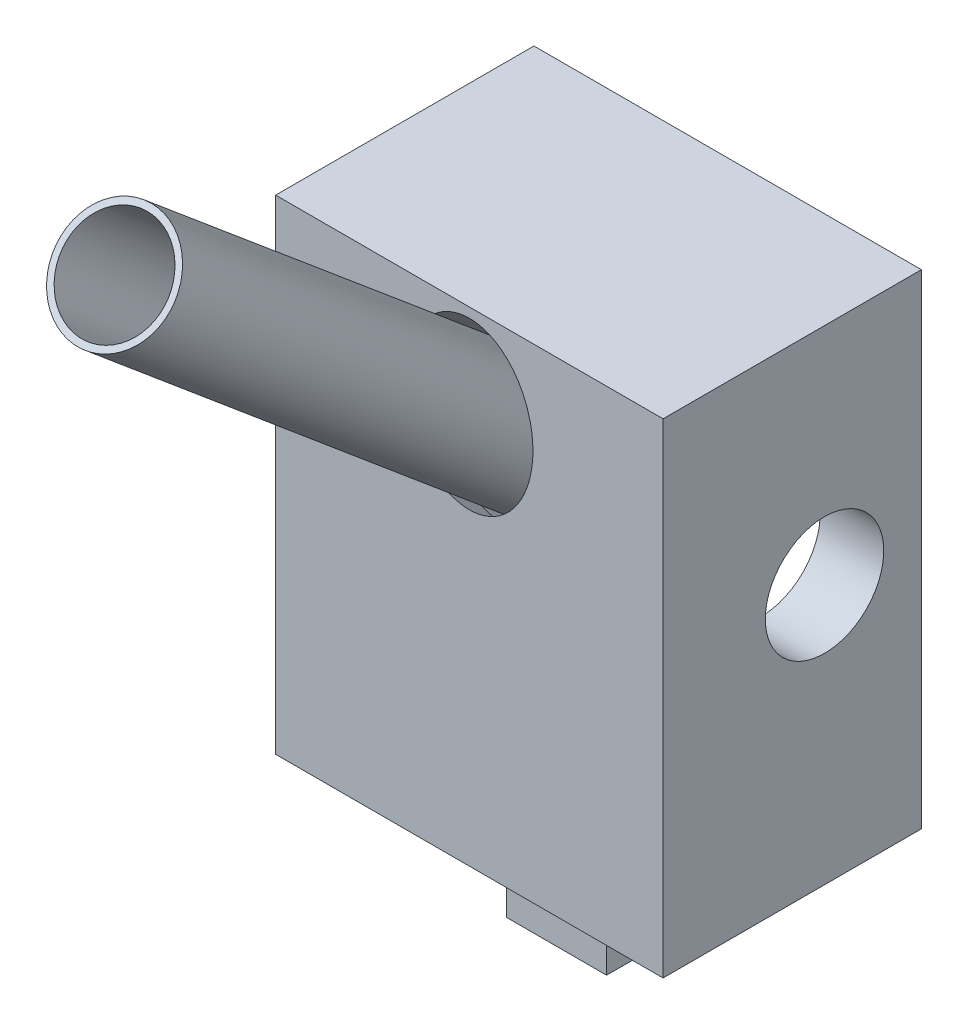
SolidWorks part; units mm, degrees
ref_plane "Front Plane" through (0, 0, 0) normal (0, 0, 1) x (1, 0, 0)
ref_plane "Top Plane" through (0, 0, 0) normal (0, 1, 0) x (1, 0, 0)
ref_plane "Right Plane" through (0, 0, 0) normal (1, 0, 0) x (0, 0, -1)
sketch "Sketch1" plane through (0, 0, 0) normal (0, 0, 1) x (1, 0, 0)
  line L1 (6066.2942, -5703.2258) -> (6096.7742, -5703.2258)
  line L2 (6066.2942, -5703.2258) -> (6066.2942, -5741.3258)
  line L3 (6066.2942, -5741.3258) -> (6096.7742, -5741.3258)
  line L4 (6096.7742, -5703.2258) -> (6096.7742, -5741.3258)
  dimension "D1" = 38.1
  dimension "D2" = 30.48
extrude "Boss-Extrude1" add sketch "Sketch1" along normal blind 20.32 from offset 7.5
sketch "Sketch2" plane through (0, 0, 7.5) normal (0, 0, -1) x (-1, 0, 0)
  line L0 (-6091.7742, -5710.8458) -> (-6096.7742, -5710.8458) construction
  line L1 (-6091.7742, -5710.8458) -> (-6071.3742, -5710.8458)
  line L2 (-6091.7742, -5710.8458) -> (-6091.7742, -5733.7058)
  line L3 (-6091.7742, -5733.7058) -> (-6071.3742, -5733.7058)
  line L4 (-6071.3742, -5710.8458) -> (-6071.3742, -5733.7058)
  line L5 (-6096.7742, -5741.3258) -> (-6096.7742, -5703.2258) construction
  line L6 (-6091.7742, -5710.8458) -> (-6091.7742, -5703.2258) construction
  line L7 (-6096.7742, -5703.2258) -> (-6066.2942, -5703.2258) construction
  line L8 (-6071.3742, -5710.8458) -> (-6066.2942, -5710.8458) construction
  line L9 (-6066.2942, -5703.2258) -> (-6066.2942, -5741.3258) construction
  line L10 (-6091.7742, -5733.7058) -> (-6091.7742, -5741.3258) construction
  line L11 (-6066.2942, -5741.3258) -> (-6096.7742, -5741.3258) construction
  dimension "D1" = 5
  dimension "D2" = 5.08
  dimension "D3" = 7.62
extrude "Cut-Extrude1" cut sketch "Sketch2" against normal blind 17.78
ref_plane "Plane3" through (0, -2342.7368, -2791.965) normal (0, -0.6428, -0.766) x (-1, 0, 0)
sketch "Sketch5" plane through (0, -2342.7368, -2791.965) normal (0, -0.6428, -0.766) x (-1, 0, 0)
  line L0 (-6081.5342, -4392.3948) -> (-6096.7742, -4392.3948) construction
  line L2 (-6081.5342, -4392.3948) -> (-6066.2942, -4392.3948) construction
  line L4 (-6066.2942, -4386.8068) -> (-6066.2942, -4415.9931) construction
  line L5 (-6096.7742, -4415.9931) -> (-6096.7742, -4386.8068) construction
  line L6 (-6081.5342, -4392.3948) -> (-6081.5342, -4386.8068) construction
  line L9 (-6096.7742, -4386.8068) -> (-6066.2942, -4386.8068) construction
  circle A0 centre (-6081.5342, -4392.3948) radius 5
  point P2 (-6081.5342, -4392.3948)
  point P5 (-6081.5342, -4386.8068)
  point P6 (-6081.5342, -4391.3807)
  point P7 (-6081.5342, -4392.4626)
  point P10 (0, 0)
  point P13 (-6081.5342, -4394.3882)
  point P14 (-6081.5342, -4386.8068)
  dimension "D1" = 10
  dimension "D2" = 5.588
extrude "Cut-Extrude2" cut sketch "Sketch5" along normal blind 23
sketch "Sketch10" plane through (0, -2342.7368, -2791.965) normal (0, -0.6428, -0.766) x (-1, 0, 0)
  line L0 (-6081.5342, -4392.3948) -> (-6096.7742, -4392.3948) construction
  line L2 (-6081.5342, -4392.3948) -> (-6066.2942, -4392.3948) construction
  circle A0 centre (-6081.5342, -4392.3948) radius 4.5
  circle A3 centre (-6081.5342, -4392.3948) radius 5 construction
  point P2 (-6084.5337, -4401.1393)
  dimension "D1" = 9
extrude "Boss-Extrude2" add sketch "Sketch10" against normal blind 31.75 and the other way blind 21.59 separate body
sketch "Sketch11" plane through (0, -2356.6146, -2808.5039) normal (0, -0.6428, -0.766) x (1, 0, 0)
  line L0 (6081.5342, 4387.8948) -> (6081.5342, 4392.3948) construction
  line L1 (6086.0342, 4392.3948) -> (6071.072, 4392.3948) construction
  circle A0 centre (6081.5342, 4392.3948) radius 4.5 construction
  circle A1 centre (6081.5342, 4392.3948) radius 4
  dimension "D1" = 8
extrude "Cut-Extrude6" cut sketch "Sketch11" against normal through all
hole_wizard "CSK for M3 Flat Head Machine Screw1" positions "Sketch13" profile "Sketch14" countersink size "M3" standard "ANSI Metric"
sketch "Sketch13" plane through (0, 0, 7.5) normal (0, 0, -1) x (-1, 0, 0)
  line L8 (-6070.1042, -5707.0358) -> (-6070.1042, -5703.2258) construction
  line L9 (-6096.7742, -5703.2258) -> (-6066.2942, -5703.2258) construction
  line L11 (-6070.1042, -5707.0358) -> (-6066.2942, -5707.0358) construction
  line L12 (-6066.2942, -5703.2258) -> (-6066.2942, -5741.3258) construction
  line L14 (-6096.7742, -5707.0358) -> (-6092.9642, -5707.0358) construction
  line L15 (-6096.7742, -5741.3258) -> (-6096.7742, -5703.2258) construction
  line L16 (-6092.9642, -5707.0358) -> (-6092.9642, -5703.2258) construction
  line L18 (-6096.7742, -5737.5158) -> (-6092.9642, -5737.5158) construction
  line L19 (-6092.9642, -5737.5158) -> (-6092.9642, -5741.3258) construction
  line L20 (-6066.2942, -5741.3258) -> (-6096.7742, -5741.3258) construction
  line L22 (-6070.1042, -5737.5158) -> (-6070.1042, -5741.3258) construction
  line L24 (-6070.1042, -5737.5158) -> (-6066.2942, -5737.5158) construction
  point P0 (-6092.9642, -5707.0358)
  point P2 (-6070.1042, -5707.0358)
  point P4 (-6070.1042, -5737.5158)
  point P6 (-6092.9642, -5737.5158)
  point P13 (-6092.9642, -5707.0358)
  dimension "D1" = 3.81
  dimension "D2" = 3.81
sketch "Sketch14" plane through (6092.9642, -5707.0358, 7.5) normal (1, 0, 0) x (0, 1, 0)
  line L0 (0, 0) -> (0, 9.906)
  line L1 (0, 9.906) -> (1.7, 8.8845)
  line L2 (1.7, 8.8845) -> (1.7, 1.45)
  line L3 (1.7, 1.45) -> (3.15, 0)
  line L5 (3.15, 0) -> (0, 0)
  line L6 (-1.7, 1.45) -> (-3.15, 0) construction
  line L10 (0, 9.906) -> (-1.7, 8.8845) construction
  line L11 (0, -6.35) -> (0, 107.95) construction
  dimension "Hole Dia." = 3.4
  dimension "Hole Depth" = 9.906
  dimension "Near C'Sink Dia." = 6.3
  dimension "Near C'Sink Angle" = 90
  dimension "Drill Angle" = 118
sketch "Sketch17" plane through (6096.7742, 0, 0) normal (1, 0, 0) x (0, 0, -1)
  line L0 (-7.5, -5741.3258) -> (-7.5, -5703.2258) construction
  circle A0 centre (-15.12, -5720.8998) radius 4.6596
  point P4 (-20.2, -5732.6203)
  point P5 (-20.2, -5732.8856)
  point P6 (-20.2, -5733.104)
  point P7 (-20.2, -5732.89)
  point P8 (-20.2, -5733.0925)
  point P9 (-15.12, -5727.9927)
  point P10 (-15.12, -5725.7169)
  point P11 (-15.12, -5723.1494)
  point P12 (-15.12, -5722.1125)
  point P13 (-15.12, -5720.8998)
  dimension "D1" = 7.62
extrude "Cut-Extrude7" cut sketch "Sketch17" against normal through all
sketch "Sketch18" plane through (0, 0, 25.28) normal (0, 0, -1) x (-1, 0, 0)
  line L0 (-6081.5742, -5733.7058) -> (-6081.5742, -5713.8505) construction
  line L5 (-6084.9947, -5713.1171) -> (-6078.2108, -5713.1171)
  line L6 (-6084.9947, -5713.1171) -> (-6084.9947, -5731.521)
  line L7 (-6084.9947, -5731.521) -> (-6078.2108, -5731.521)
  line L8 (-6078.2108, -5713.1171) -> (-6078.2108, -5731.521)
  line L9 (-6084.9947, -5713.1171) -> (-6078.2108, -5731.521) construction
  line L10 (-6084.9947, -5731.521) -> (-6078.2108, -5713.1171) construction
  point P2 (-6078.2108, -5731.2459)
  point P3 (-6084.9947, -5731.2459)
  point P12 (-6068.1657, -5740.4658)
  point P13 (-6081.5742, -5713.5017)
  point P14 (-6081.5742, -5714.0932)
  point P15 (-6081.5742, -5710.1508)
  point P16 (-6081.5742, -5710.9127)
sketch "Sketch19" plane through (0, -5741.3258, 0) normal (0, -1, 0) x (1, 0, 0)
  line L0 (6066.2942, 17.66) -> (6096.7742, 17.66) construction
  line L1 (6066.2942, 27.82) -> (6066.2942, 7.5) construction
  line L2 (6096.7742, 27.82) -> (6096.7742, 7.5) construction
  line L3 (6081.5342, 17.66) -> (6081.5342, 27.82) construction
  line L4 (6066.2942, 27.82) -> (6096.7742, 27.82) construction
  line L6 (6077.5972, 20.962) -> (6085.4712, 20.962)
  line L7 (6077.5972, 20.962) -> (6077.5972, 14.358)
  line L8 (6077.5972, 14.358) -> (6085.4712, 14.358)
  line L9 (6085.4712, 20.962) -> (6085.4712, 14.358)
  line L10 (6077.5972, 20.962) -> (6085.4712, 14.358) construction
  line L11 (6077.5972, 14.358) -> (6085.4712, 20.962) construction
  dimension "D1" = 7.874
  dimension "D2" = 6.604
extrude "Boss-Extrude3" add sketch "Sketch19" along normal blind 8.89
sketch "Sketch22" plane through (6066.2942, 0, 0) normal (-1, 0, 0) x (0, 0, 1)
  line L1 (-22.98, -5754.09) -> (27.82, -5754.09)
  line L2 (-22.98, -5754.09) -> (-22.98, -5693.7611)
  line L3 (-22.98, -5693.7611) -> (27.82, -5693.7611)
  line L4 (27.82, -5754.09) -> (27.82, -5693.7611)
  line L5 (27.82, -5703.2258) -> (27.82, -5741.3258) construction
  point P7 (27.82, -5741.3258)
  point P8 (27.82, -5745.1553)
  point P9 (27.82, -5755.4363)
  point P10 (27.82, -5751.2323)
  point P11 (27.82, -5754.09)
  point P12 (0, 0)
  dimension "D1" = 50.8
sketch "Sketch23" plane through (0, 0, 14.358) normal (0, 0, -1) x (-1, 0, 0)
  line L1 (-6085.4712, -5744.4795) -> (-6077.5972, -5744.4795)
  line L2 (-6085.4712, -5744.4795) -> (-6085.4712, -5750.2158)
  line L3 (-6085.4712, -5750.2158) -> (-6077.5972, -5750.2158)
  line L4 (-6077.5972, -5744.4795) -> (-6077.5972, -5750.2158)
